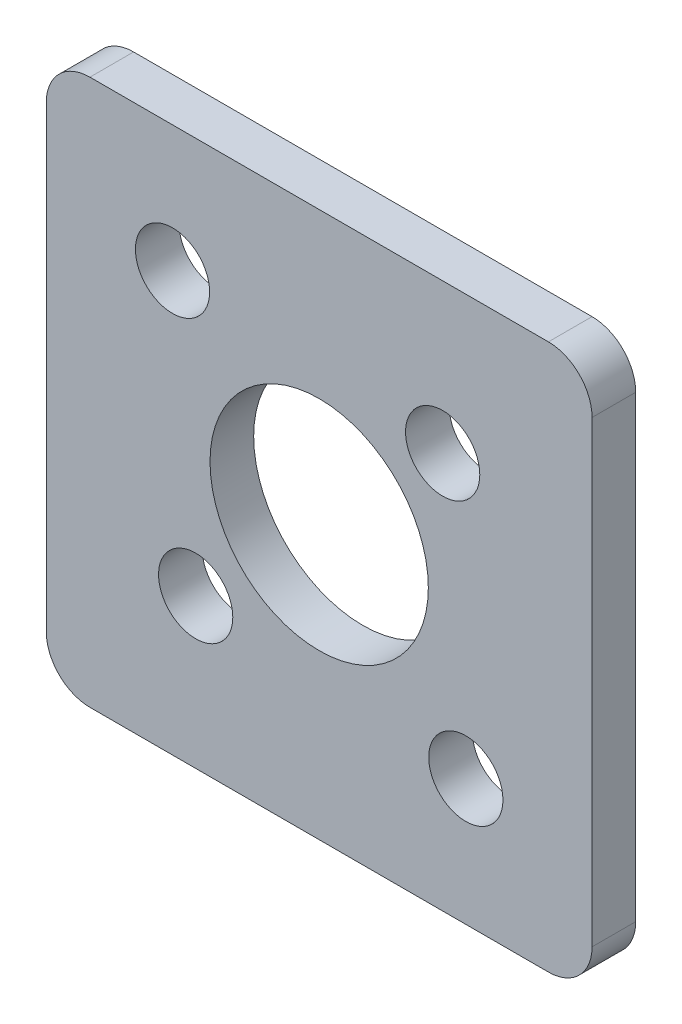
SolidWorks part; units mm, degrees
ref_plane "Front Plane" through (0, 0, 0) normal (0, 0, 1) x (1, 0, 0)
ref_plane "Top Plane" through (0, 0, 0) normal (0, 1, 0) x (1, 0, 0)
ref_plane "Right Plane" through (0, 0, 0) normal (1, 0, 0) x (0, 0, -1)
sketch "Sketch1" plane through (0, 0, 0) normal (0, 0, 1) x (1, 0, 0)
  line L0 (6.7175, -6.7175) -> (-6.7175, 6.7175) construction
  line L5 (-5.6569, -5.6569) -> (5.6569, 5.6569) construction
  line L7 (-12.5, -12.5) -> (12.5, -12.5)
  line L8 (-12.5, -12.5) -> (-12.5, 12.5)
  line L9 (-12.5, 12.5) -> (12.5, 12.5)
  line L10 (12.5, -12.5) -> (12.5, 12.5)
  circle A5 centre (0, 0) radius 5
  point P6 (0, 0)
  point P8 (0, 0)
  point P9 (0, 12.5)
  point P14 (-12.5, 0)
  point P15 (5.2708, 7.9037)
  point P16 (-8.6829, 8.992)
  point P17 (0, 0)
  point P18 (-9.0042, 8.6704)
  point P20 (0, 0)
  dimension "D1" = 10
  dimension "D2" = 19
  dimension "D3" = 16
  dimension "D4" = 25
extrude "Boss-Extrude2" add sketch "Sketch1" along normal blind 2
fillet "Fillet2" radius 2 4 edges at (12.5, -12.5, 1) (-12.5, -12.5, 1) (-12.5, 12.5, 1) (12.5, 12.5, 1)
hole_wizard "M3 Clearance Hole1" positions "Sketch2" profile "Sketch3" hole size "M3" standard "ANSI Metric" end condition through all
sketch "Sketch2" plane through (0, 0, 2) normal (0, 0, 1) x (1, 0, 0)
  point P0 (-6.7175, 6.7175)
  point P3 (5.6569, 5.6569)
  point P6 (6.7175, -6.7175)
  point P9 (-5.6569, -5.6569)
sketch "Sketch3" plane through (-6.7175, 6.7175, 2) normal (1, 0, 0) x (0, -1, 0)
  line L0 (0, 0) -> (0, 2)
  line L1 (0, 2) -> (1.7, 2)
  line L2 (1.7, 2) -> (1.7, 0)
  line L5 (1.7, 0) -> (0, 0)
  line L11 (0, -6.35) -> (0, 107.95) construction
  dimension "Thru Hole Dia." = 3.4
  dimension "Thru Hole Depth" = 2
